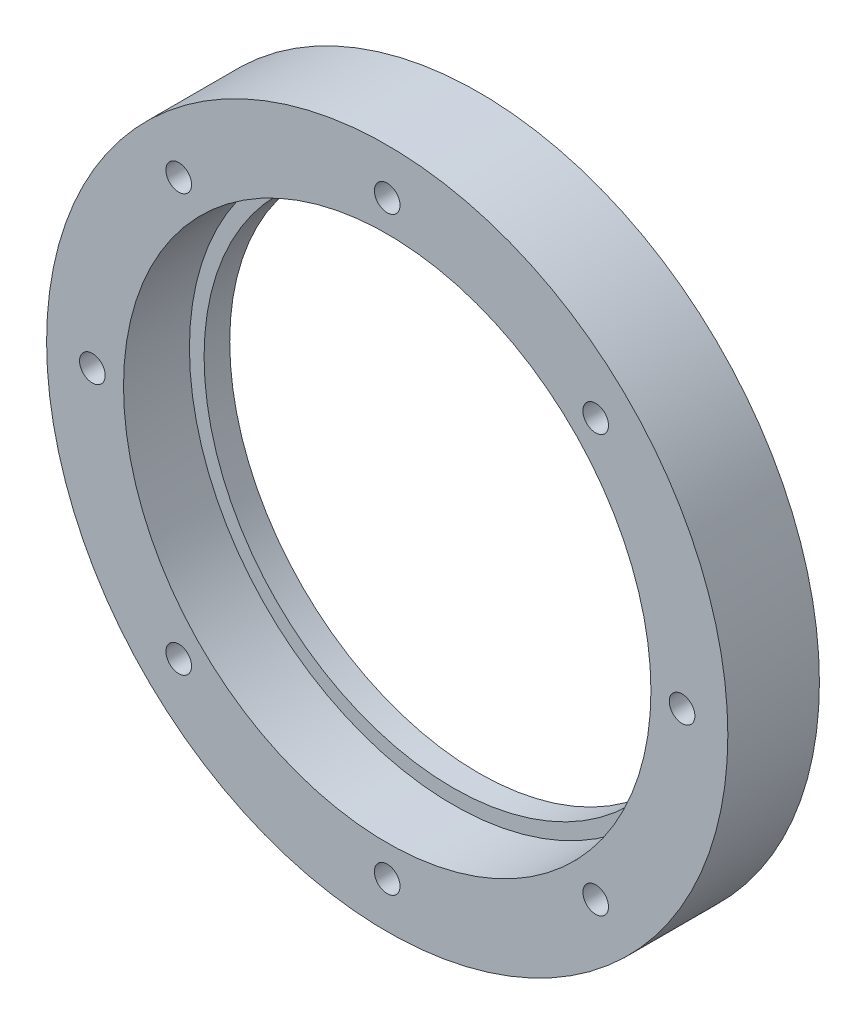
SolidWorks part; units mm, degrees
material "6061-T6 (SS)"
ref_plane "Front Plane" through (0, 0, 0) normal (0, 0, 1) x (1, 0, 0)
ref_plane "Top Plane" through (0, 0, 0) normal (0, 1, 0) x (1, 0, 0)
ref_plane "Right Plane" through (0, 0, 0) normal (1, 0, 0) x (0, 0, -1)
sketch "Sketch1" plane through (0, 0, 0) normal (0, 0, 1) x (1, 0, 0)
  circle A0 centre (0, 0) radius 46.5
  circle A2 centre (0, 0) radius 36
  dimension "D1" = 93
  dimension "D2" = 72
extrude "Boss-Extrude1" add sketch "Sketch1" along normal mid plane 12.5
sketch "Sketch4" plane through (0, 0, -6.25) normal (0, 0, 1) x (1, 0, 0)
  circle A0 centre (0, 0) radius 34
  circle A1 centre (0, 0) radius 36 construction
  circle A2 centre (0, 0) radius 36
  dimension "D1" = 68
extrude "Boss-Extrude2" add sketch "Sketch4" along normal offset from surface (3.5 mm away) 9 up to face at (46.5, 0, 6.25)
sketch "Sketch3" plane through (0, 0, 6.25) normal (0, 0, 1) x (1, 0, 0)
  circle A2 centre (0, 40.25) radius 1.75
  circle A12 centre (0, 0) radius 40.25 construction
  dimension "D1" = 80.5
  dimension "D3" = 3.5
extrude "Cut-Extrude1" cut sketch "Sketch3" against normal through all
pattern_circular "CirPattern1" count 8 over 360 about axis through (0, 0, 0) along (0, 0, 1) of "Cut-Extrude1"
